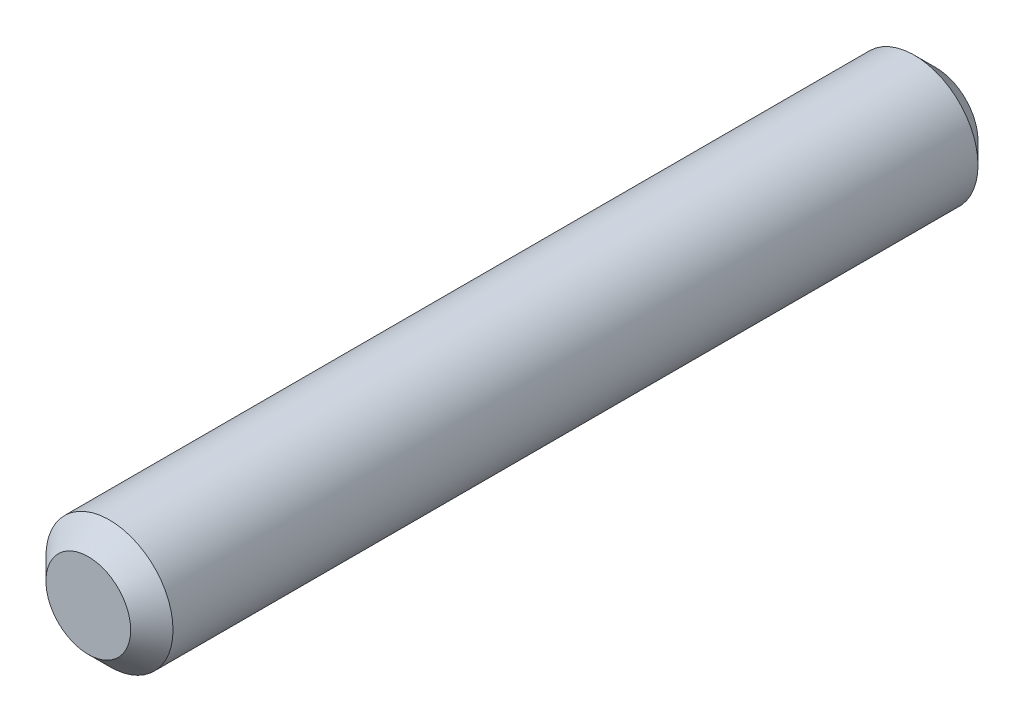
SolidWorks part; units mm, degrees
ref_plane "Спереди" through (0, 0, 0) normal (0, 0, 1) x (1, 0, 0)
ref_plane "Сверху" through (0, 0, 0) normal (0, 1, 0) x (1, 0, 0)
ref_plane "Справа" through (0, 0, 0) normal (1, 0, 0) x (0, 0, -1)
sketch "Эскиз1" plane through (0, 0, 0) normal (0, 0, 1) x (1, 0, 0)
  circle A0 centre (0, 0) radius 1.5
  point P2 (0, 0)
  dimension "D1" = 3
extrude "Бобышка-Вытянуть1" add sketch "Эскиз1" along normal blind 20
chamfer "Фаска1" distance 0.5 angle 45 2 edges at (1.5, 0, 0) (1.5, 0, 20)
